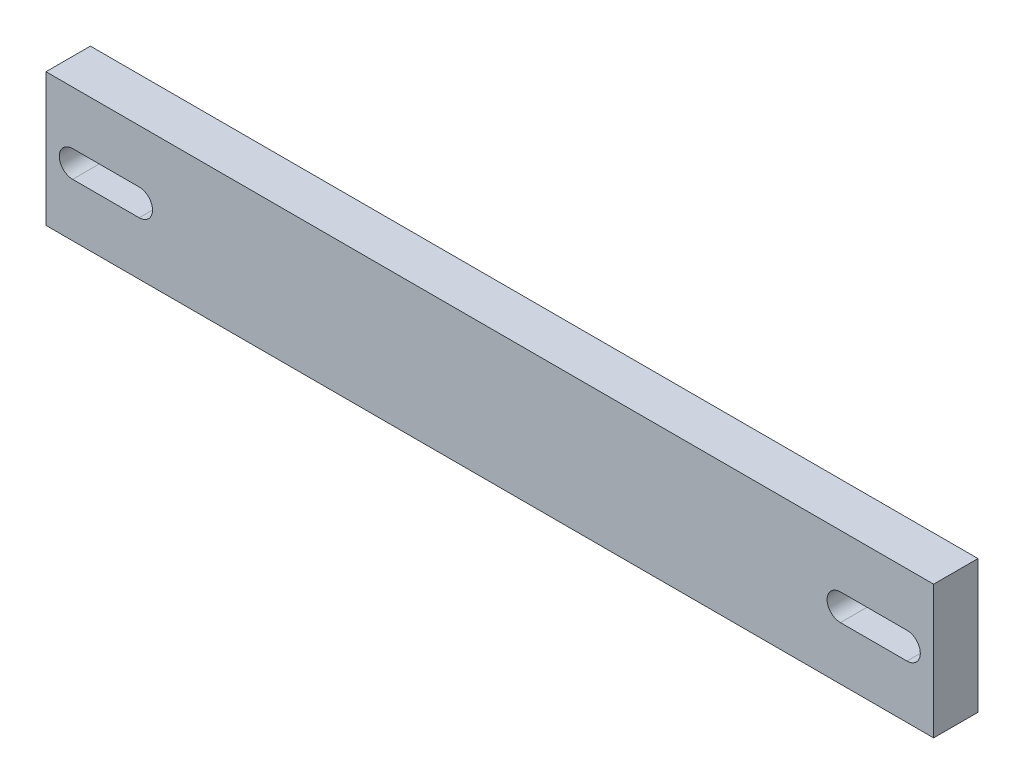
SolidWorks part; units mm, degrees
material "Alloy Steel"
ref_plane "Front Plane" through (0, 0, 0) normal (0, 0, 1) x (1, 0, 0)
ref_plane "Top Plane" through (0, 0, 0) normal (0, 1, 0) x (1, 0, 0)
ref_plane "Right Plane" through (0, 0, 0) normal (1, 0, 0) x (0, 0, -1)
sketch "Sketch1" plane through (0, 0, 0) normal (0, 0, 1) x (1, 0, 0)
  line L1 (-100, -15) -> (100, -15)
  line L2 (-100, -15) -> (-100, 15)
  line L3 (-100, 15) -> (100, 15)
  line L4 (100, -15) -> (100, 15)
  line L5 (-100, -15) -> (100, 15) construction
  line L6 (-100, 15) -> (100, -15) construction
  line L9 (-103.7461, 0) -> (111.7297, 0) construction
  line L10 (-94, 0) -> (-79, 0) construction
  line L11 (-94, 3) -> (-79, 3)
  line L12 (-94, -3) -> (-79, -3)
  line L13 (0, 76.2496) -> (0, -42.0552) construction
  line L14 (94, 0) -> (79, 0) construction
  line L15 (94, 3) -> (79, 3)
  line L16 (94, -3) -> (79, -3)
  arc A0 (-94, 3) -> (-94, -3) centre (-94, 0) ccw
  arc A1 (-79, -3) -> (-79, 3) centre (-79, 0) ccw
  arc A2 (94, 3) -> (94, -3) centre (94, 0) cw
  arc A3 (79, -3) -> (79, 3) centre (79, 0) cw
  point P0 (0, 0)
  point P9 (0, 0)
  point P14 (-86.5, 0)
  point P23 (86.5, 0)
  dimension "D3" = 3
  dimension "D4" = 15
  dimension "D1" = 30
  dimension "D2" = 200
  dimension "D5" = 94
extrude "Boss-Extrude1" add sketch "Sketch1" along normal blind 10
